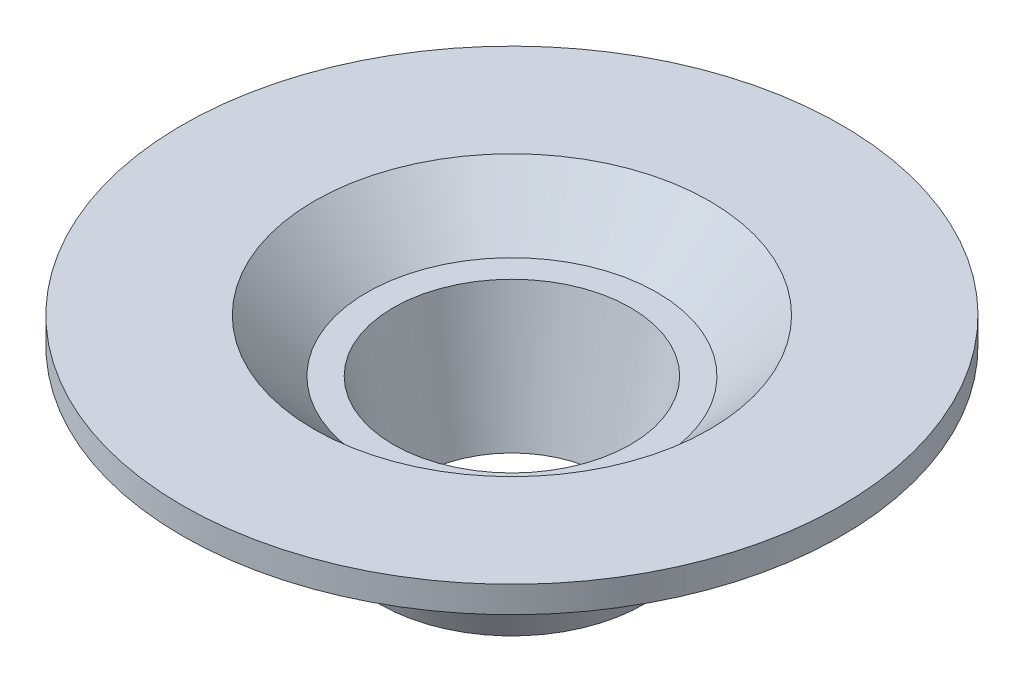
SolidWorks part; units mm, degrees
ref_plane "Front Plane" through (0, 0, 0) normal (0, 0, 1) x (1, 0, 0)
ref_plane "Top Plane" through (0, 0, 0) normal (0, 1, 0) x (1, 0, 0)
ref_plane "Right Plane" through (0, 0, 0) normal (1, 0, 0) x (0, 0, -1)
sketch "Sketch1" plane through (0, 0, 0) normal (1, 0, 0) x (0, 0, -1)
  line L0 (0, 0) -> (0, -5) construction
  line L1 (4.5, 0) -> (3.5, -5)
  line L2 (3.5, -5) -> (5, -5)
  line L3 (5, -5) -> (6.5, -1)
  line L4 (6.5, -1) -> (8.5, -1)
  line L5 (8.5, -1) -> (10.5, 1)
  line L6 (10.5, 1) -> (12.5, 1)
  line L7 (12.5, 1) -> (12.5, 2)
  line L8 (12.5, 2) -> (7.5, 2)
  line L9 (7.5, 2) -> (5.5, 0)
  line L10 (5.5, 0) -> (4.5, 0)
  point P13 (0, 0)
  point P14 (5.5535, 2.3225)
  point P15 (4.4931, 0)
  point P16 (5.5535, 0)
  point P17 (8.7345, 3.3829)
  dimension "D1" = 5
  dimension "D2" = 12.5
  dimension "D3" = 1.5
  dimension "D4" = 3.5
  dimension "D5" = 4.5
  dimension "D6" = 6.5
  dimension "D7" = 4
  dimension "D8" = 2
  dimension "D9" = 2
  dimension "D10" = 1
  dimension "D11" = 2
  dimension "D12" = 1
revolve "Revolve1" add sketch "Sketch1" angle 360 about L0
